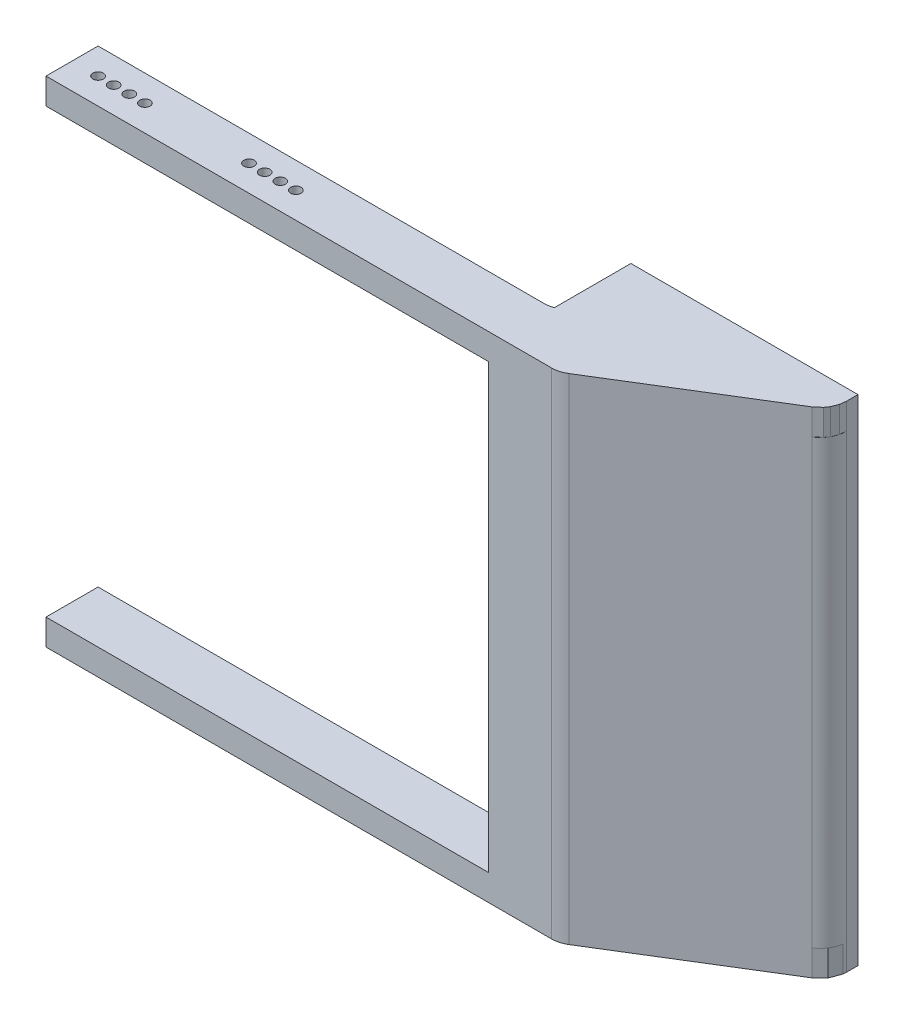
SolidWorks part; units mm, degrees
other "Marquage1"
sketch "Esquisse6" plane through (-75, 0, -38.2843) normal (-0.024, -0.0063, -0.9997) x (-0.9942, -0.1051, 0.0245)
ref_plane "Front Plane" through (0, 0, 0) normal (0, 0, 1) x (1, 0, 0)
ref_plane "Top Plane" through (0, 0, 0) normal (0, 1, 0) x (1, 0, 0)
ref_plane "Right Plane" through (0, 0, 0) normal (1, 0, 0) x (0, 0, -1)
sketch "Sketch1" plane through (0, 0, 0) normal (0, 1, 0) x (1, 0, 0)
  line L0 (-52.25, 0) -> (52.25, 0) construction
  line L1 (30, 0) -> (-75, 0)
  line L4 (-75, 0) -> (-75, 10)
  line L5 (30, 10) -> (55.9808, 25)
  line L6 (55.9808, 25) -> (55.9808, 20)
  line L7 (55.9808, 20) -> (28.4498, 3.0365)
  line L8 (30, 10) -> (12.5, 25)
  line L9 (12.5, 25) -> (12.5, 20)
  line L10 (12.5, 20) -> (24.1667, 10)
  line L11 (28.4498, 3.0365) -> (23.5217, 0)
  line L12 (-75, 10) -> (24.1667, 10)
  line L13 (23.5217, 0) -> (-75, 0)
  line L14 (24.1667, 10) -> (30, 10)
  dimension "D10" = 10
  dimension "D1" = 30
  dimension "D2" = 30
  dimension "D3" = 75
  dimension "D4" = 10
  dimension "D5" = 20
  dimension "D6" = 30
  dimension "D7" = 5
  dimension "D8" = 20
  dimension "D9" = 5
  dimension "D11" = 109.399
extrude "Boss-Extrude3" add sketch "Sketch1" along normal blind 95 contours L4 L12 L10 L9 L8 L5 L6 L7 L11 L13
fillet "Fillet8" radius 5 1 edges at (24.1667, 47.5, -10)
fillet "Fillet9" radius 5 2 edges at (55.9808, 47.5, -20) (12.5, 47.5, -20)
fillet "Fillet10" radius 5 1 edges at (23.5217, 47.5, 0)
sketch "Esquisse3" plane through (0, 0, -10) normal (0, 0, -1) x (-1, 0, 0)
  line L0 (75, 95) -> (75, 0) construction
  line L1 (75, 5) -> (45, 5)
  line L2 (75, 5) -> (75, 90)
  line L3 (75, 90) -> (45, 90)
  line L4 (45, 5) -> (45, 90)
  line L5 (75, 0) -> (-10.6504, 0) construction
  line L6 (75, 95) -> (-10.6504, 95) construction
  dimension "D1" = 5
  dimension "D2" = 5
  dimension "D3" = 30
extrude "Enlèv. mat.-Extru.1" cut sketch "Esquisse3" against normal through all contours L2 L1 L4 L3
sketch "Esquisse5" plane through (0, 0, -10) normal (0, 0, -1) x (-1, 0, 0)
  line L1 (45, 5) -> (35, 5)
  line L2 (45, 5) -> (45, 65)
  line L3 (45, 65) -> (35, 65)
  line L4 (35, 5) -> (35, 65)
  dimension "D1" = 10
extrude "Enlèv. mat.-Extru.2" cut sketch "Esquisse5" against normal through all contours L2 L1 L4 L3
sketch "Esquisse14" plane through (0, 0, -10) normal (0, 0, -1) x (-1, 0, 0)
  line L0 (45, 65) -> (35, 65) construction
  line L1 (45, 90) -> (35, 90)
  line L2 (45, 90) -> (45, 65)
  line L3 (45, 65) -> (35, 65)
  line L4 (35, 90) -> (35, 65)
extrude "Enlèv. mat.-Extru.7" cut sketch "Esquisse14" against normal through all
sketch "Esquisse15" plane through (0, 0, -10) normal (0, 0, -1) x (-1, 0, 0)
  line L1 (35, 90) -> (5, 90)
  line L2 (35, 90) -> (35, 5)
  line L3 (35, 5) -> (5, 5)
  line L4 (5, 90) -> (5, 5)
  dimension "D1" = 30
extrude "Enlèv. mat.-Extru.8" cut sketch "Esquisse15" against normal through all
sketch "Esquisse21" plane through (0, 0, -10) normal (0, 0, -1) x (-1, 0, 0)
  line L1 (5, 90) -> (-10, 90)
  line L2 (5, 90) -> (5, 5)
  line L3 (5, 5) -> (-10, 5)
  line L4 (-10, 90) -> (-10, 5)
  dimension "D1" = 15
extrude "Enlèv. mat.-Extru.9" cut sketch "Esquisse21" against normal through all
sketch "Esquisse61" plane through (0, 0, 0) normal (0, 1, 0) x (1, 0, 0)
  line L1 (12.2705, 25) -> (55.9406, 25)
  line L2 (12.2705, 25) -> (12.2705, 4.0617)
  line L3 (12.2705, 4.0617) -> (55.9406, 4.0617)
  line L4 (55.9406, 25) -> (55.9406, 4.0617)
extrude "Boss.-Extru.3" add sketch "Esquisse61" along normal blind 5
sketch "Esquisse63" plane through (0, 5, 0) normal (0, 1, 0) x (1, 0, 0)
  line L0 (55.9406, 22.16) -> (55.183, 20.0827)
  line L1 (55.183, 20.0827) -> (53.6036, 18.5353)
  line L2 (53.6036, 18.5353) -> (30.1137, 4.0617)
  line L3 (30.1137, 4.0617) -> (55.9406, 4.0617)
  line L4 (55.9406, 4.0617) -> (55.9406, 22.16)
  arc A0 (53.6036, 18.5353) -> (55.9406, 22.16) centre (50.9808, 22.7921) ccw construction
extrude "Enlèv. mat.-Extru.18" cut sketch "Esquisse63" against normal blind 5
sketch "Esquisse69" plane through (0, 95, 0) normal (0, 1, 0) x (1, 0, 0)
  line L1 (55.9808, 25) -> (12.3569, 25)
  line L2 (55.9808, 25) -> (55.9808, 7.8571)
  line L3 (55.9808, 7.8571) -> (12.3569, 7.8571)
  line L4 (12.3569, 25) -> (12.3569, 7.8571)
extrude "Boss.-Extru.4" add sketch "Esquisse69" against normal blind 5
sketch "Esquisse71" plane through (0, 90, 0) normal (0, -1, 0) x (1, 0, 0)
  line L0 (55.9808, -22.7921) -> (55.8261, -21.5582)
  line L1 (55.8261, -21.5582) -> (55.3462, -20.3543)
  line L2 (55.3462, -20.3543) -> (54.8122, -19.5797)
  line L3 (54.8122, -19.5797) -> (53.6036, -18.5353)
  line L4 (53.6036, -18.5353) -> (36.2734, -7.8571)
  line L5 (36.2734, -7.8571) -> (55.9808, -7.8571)
  line L6 (55.9808, -7.8571) -> (55.9808, -22.7921)
  arc A0 (55.9808, -22.7921) -> (53.6036, -18.5353) centre (50.9808, -22.7921) ccw construction
extrude "Enlèv. mat.-Extru.21" cut sketch "Esquisse71" against normal blind 10
sketch "Esquisse77" plane through (3.1699, 0, 5.4904) normal (-0.5, 0, -0.866) x (-0.866, 0, 0.5)
  line L0 (-30.9808, 90) -> (-40.9808, 90)
  line L1 (-60.9808, 90) -> (-30.9808, 90) construction
  line L2 (-40.9808, 90) -> (-31.4808, 5)
  line L3 (-30.9808, 5) -> (-60.9344, 5) construction
  line L4 (-31.4808, 5) -> (-30.9808, 5)
  line L5 (-30.9808, 90) -> (-30.9808, 5) construction
  line L6 (-30.9808, 5) -> (-30.9808, 90)
  dimension "D1" = 0.5
  dimension "D2" = 10
extrude "Boss.-Extru.7" add sketch "Esquisse77" along normal blind 17
sketch "Esquisse79" plane through (0, 90, 0) normal (0, 1, 0) x (1, 0, 0)
  line L0 (21.9808, 25) -> (32.8868, 25)
  line L1 (32.8868, 25) -> (30.1603, 29.7224)
  line L2 (30.1603, 29.7224) -> (21.9808, 25)
extrude "Enlèv. mat.-Extru.25" cut sketch "Esquisse79" against normal up to next and the other way through all
sketch "Esquisse80" plane through (0, 5, 0) normal (0, 1, 0) x (1, 0, 0)
  line L3 (12.5, 25) -> (30, 10)
  line L4 (30, 10) -> (21.25, 25)
  line L5 (55.9406, 25) -> (12.5, 25) construction
  line L6 (21.25, 25) -> (12.5, 25)
extrude "Boss.-Extru.10" add sketch "Esquisse80" along normal blind 86
sketch "Esquisse84" plane through (0, 90, 0) normal (0, -1, 0) x (-1, 0, 0)
  line L0 (75, 0) -> (75, 10) construction
  line L1 (75, 0) -> (-10, 0) construction
  circle A0 centre (70, 5) radius 1
  circle A1 centre (67, 5) radius 1
  circle A2 centre (64, 5) radius 1
  circle A3 centre (61, 5) radius 1
  circle A4 centre (41, 5) radius 1
  circle A5 centre (38, 5) radius 1
  circle A6 centre (35, 5) radius 1
  circle A7 centre (32, 5) radius 1
  dimension "D2" = 2
  dimension "D1" = 5
  dimension "D3" = 5
  dimension "D4" = 3
  dimension "D5" = 3
  dimension "D6" = 3
  dimension "D7" = 20
  dimension "D8" = 3
  dimension "D9" = 3
  dimension "D10" = 3
extrude "Enlèv. mat.-Extru.26" cut sketch "Esquisse84" against normal through all
